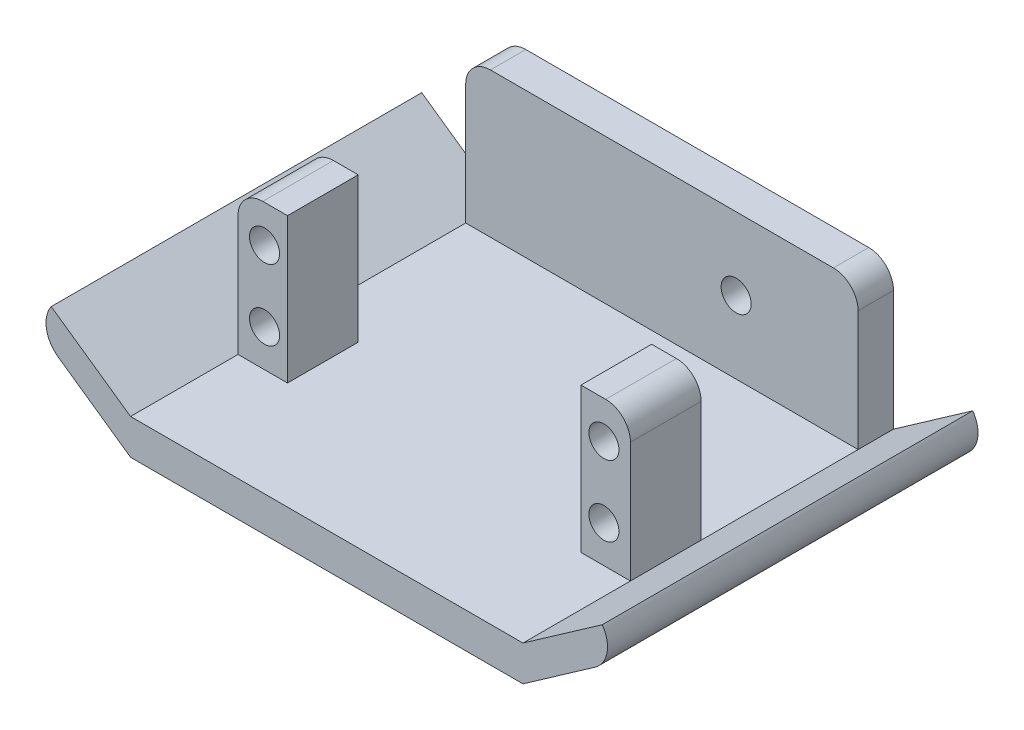
SolidWorks part; units mm, degrees
ref_plane "Front" through (0, 0, 0) normal (0, 0, 1) x (1, 0, 0)
ref_plane "Top" through (0, 0, 0) normal (0, 1, 0) x (1, 0, 0)
ref_plane "Right" through (0, 0, 0) normal (1, 0, 0) x (0, 0, -1)
sketch "Sketch1" plane through (0, 0, 0) normal (0, 1, 0) x (1, 0, 0)
  line L1 (0, 0) -> (55.5, 0)
  line L2 (0, 0) -> (0, 40.4)
  line L3 (0, 40.4) -> (55.5, 40.4)
  line L4 (55.5, 0) -> (55.5, 40.4)
  dimension "D1" = 55.5
  dimension "D2" = 40.4
extrude "base" add sketch "Sketch1" along normal blind 5
sketch "Sketch2" plane through (0, 0, -40.4) normal (0, 0, -1) x (-1, 0, 0)
  line L1 (0, 5) -> (0, 0) construction
  line L2 (-55.5, 0) -> (0, 0)
  line L3 (-55.5, 0) -> (-55.5, 25.5)
  line L4 (-55.5, 25.5) -> (0, 25.5)
  line L5 (0, 0) -> (0, 25.5)
  line L6 (-55.5, 5) -> (0, 5) construction
  dimension "D1" = 20.5
extrude "wall" add sketch "Sketch2" against normal blind 5
ref_plane "Plane1" through (0, 0, -8.2) normal (0, 0, 1) x (1, 0, 0)
sketch "Sketch3" plane through (0, 0, -8.2) normal (0, 0, 1) x (1, 0, 0)
  line L0 (0, 5) -> (55.5, 5) construction
  line L1 (0, 25.5) -> (7, 25.5)
  line L2 (0, 25.5) -> (0, 5)
  line L3 (0, 5) -> (7, 5)
  line L4 (7, 25.5) -> (7, 5)
  line L5 (27.75, 5) -> (27.75, 25.5) construction
  line L6 (55.5, 5) -> (0, 5) construction
  line L7 (0, 25.5) -> (55.5, 25.5) construction
  line L8 (55.5, 5) -> (48.5, 5)
  line L9 (48.5, 25.5) -> (48.5, 5)
  line L10 (55.5, 25.5) -> (48.5, 25.5)
  line L11 (55.5, 25.5) -> (55.5, 5)
  dimension "D1" = 7
extrude "mountingTabs" add sketch "Sketch3" along normal blind 5
sketch "Sketch4" plane through (0, 0, 0) normal (0, 0, 1) x (1, 0, 0)
  line L0 (27.75, 0) -> (27.75, 25.5) construction
  line L1 (0, 0) -> (55.5, 0) construction
  line L2 (0, 25.5) -> (55.5, 25.5) construction
  line L3 (0, 0) -> (-10.2089, 7.1483)
  line L4 (0, 5) -> (-11.2182, 12.8551)
  line L5 (0, 5) -> (0, 0)
  line L6 (55.5, 5) -> (66.7182, 12.8551)
  line L7 (55.5, 5) -> (55.5, 0)
  line L8 (55.5, 0) -> (65.7089, 7.1483)
  arc A0 (-11.2182, 12.8551) -> (-10.2089, 7.1483) centre (-7.8572, 10.5069) ccw
  arc A1 (66.7182, 12.8551) -> (65.7089, 7.1483) centre (63.3572, 10.5069) cw
  dimension "D1" = 145
  dimension "D2" = 12.4627
  dimension "D3" = 13.6949
extrude "lips" add sketch "Sketch4" against normal up to surface (40.4 mm away) up to face at (27.75, 12.75, -40.4)
sketch "Sketch5" plane through (0, 0, -3.2) normal (0, 0, 1) x (1, 0, 0)
  line L0 (27.75, 0) -> (27.75, 25.5) construction
  line L3 (0, 15.25) -> (55.5, 15.25) construction
  line L4 (0, 25.5) -> (0, 5) construction
  line L5 (55.5, 5) -> (55.5, 25.5) construction
  line L6 (7, 25.5) -> (0, 25.5) construction
  line L7 (0, 0) -> (55.5, 0) construction
  line L8 (0, 25.5) -> (55.5, 25.5) construction
  circle A0 centre (3.75, 20.25) radius 2.125
  circle A1 centre (3.75, 10.25) radius 2.125
  circle A4 centre (51.75, 10.25) radius 2.125
  circle A5 centre (51.75, 20.25) radius 2.125
  dimension "D1" = 4.25
  dimension "D2" = 5.25
  dimension "D3" = 3.75
extrude "mountingHoles" cut sketch "Sketch5" against normal blind 5
fillet "fillets" radius 3.5 4 edges at (0, 25.5, -37.9) (55.5, 25.5, -37.9) (0, 25.5, -5.7) (55.5, 25.5, -5.7)
sketch "Sketch6" plane through (0, 0, -35.4) normal (0, 0, 1) x (1, 0, 0)
  line L0 (3.5, 25.5) -> (52, 25.5) construction
  line L1 (55.5, 5) -> (55.5, 22) construction
  circle A0 centre (38.25, 15.25) radius 2.125
  dimension "D1" = 4.25
  dimension "D2" = 10.25
  dimension "D3" = 17.25
extrude "throughHole" cut sketch "Sketch6" against normal blind 5
sketch "Sketch7" plane through (0, 0, -8.2) normal (0, 0, -1) x (-1, 0, 0)
  line L4 (-48.5, 25.5) -> (-52, 25.5)
  line L5 (-55.5, 22) -> (-55.5, 5)
  line L6 (-55.5, 5) -> (-48.5, 5)
  line L7 (-48.5, 5) -> (-48.5, 25.5)
  line L8 (-48.5, 25.5) -> (-52, 25.5)
  line L9 (-55.5, 22) -> (-55.5, 5)
  line L10 (-55.5, 5) -> (-48.5, 5)
  line L11 (-48.5, 5) -> (-48.5, 25.5)
  line L12 (0, 5) -> (0, 22)
  line L13 (-3.5, 25.5) -> (-7, 25.5)
  line L14 (-7, 25.5) -> (-7, 5)
  line L15 (-7, 5) -> (0, 5)
  line L16 (0, 5) -> (0, 22)
  line L17 (-3.5, 25.5) -> (-7, 25.5)
  line L18 (-7, 25.5) -> (-7, 5)
  line L19 (-7, 5) -> (0, 5)
  circle A0 centre (-51.75, 20.25) radius 2.125 construction
  arc A1 (-52, 25.5) -> (-55.5, 22) centre (-52, 22) ccw
  arc A2 (-52, 25.5) -> (-55.5, 22) centre (-52, 22) ccw
  arc A3 (0, 22) -> (-3.5, 25.5) centre (-3.5, 22) ccw
  arc A4 (0, 22) -> (-3.5, 25.5) centre (-3.5, 22) ccw
  circle A5 centre (-51.75, 20.25) radius 2.125
  circle A6 centre (-51.75, 10.25) radius 2.125 construction
  circle A7 centre (-51.75, 10.25) radius 2.125
  circle A8 centre (-3.75, 10.25) radius 2.125 construction
  circle A9 centre (-3.75, 10.25) radius 2.125
  circle A10 centre (-3.75, 20.25) radius 2.125 construction
  circle A11 centre (-3.75, 20.25) radius 2.125
  dimension "D1" = 0
  dimension "D2" = 0
extrude "Boss-Extrude1" add sketch "Sketch7" along normal blind 5
sketch "Sketch8" plane through (0, 0, 0) normal (0, 0, 1) x (1, 0, 0)
  line L6 (0, 0) -> (55.5, 0)
  line L7 (55.5, 0) -> (65.7089, 7.1483)
  line L8 (66.7182, 12.8551) -> (55.5, 5)
  line L9 (55.5, 5) -> (0, 5)
  line L10 (0, 5) -> (-11.2182, 12.8551)
  line L11 (-10.2089, 7.1483) -> (0, 0)
  line L12 (0, 0) -> (55.5, 0)
  line L13 (55.5, 0) -> (65.7089, 7.1483)
  line L14 (66.7182, 12.8551) -> (55.5, 5)
  line L15 (55.5, 5) -> (0, 5)
  line L16 (0, 5) -> (-11.2182, 12.8551)
  line L17 (-10.2089, 7.1483) -> (0, 0)
  arc A2 (65.7089, 7.1483) -> (66.7182, 12.8551) centre (63.3572, 10.5069) ccw
  arc A3 (-11.2182, 12.8551) -> (-10.2089, 7.1483) centre (-7.8572, 10.5069) ccw
  arc A4 (65.7089, 7.1483) -> (66.7182, 12.8551) centre (63.3572, 10.5069) ccw
  arc A5 (-11.2182, 12.8551) -> (-10.2089, 7.1483) centre (-7.8572, 10.5069) ccw
  dimension "D1" = 0
extrude "Boss-Extrude2" add sketch "Sketch8" along normal blind 12
